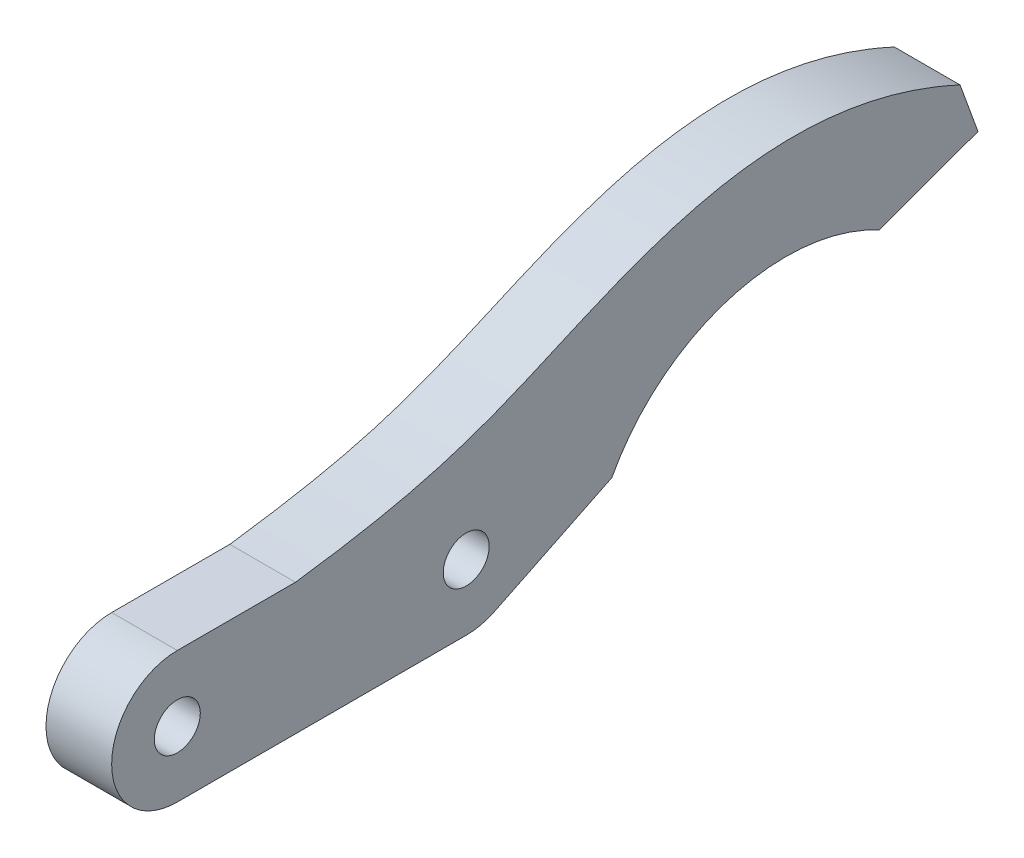
SolidWorks part; units mm, degrees
ref_plane "Front Plane" through (0, 0, 0) normal (0, 0, 1) x (1, 0, 0)
ref_plane "Top Plane" through (0, 0, 0) normal (0, 1, 0) x (1, 0, 0)
ref_plane "Right Plane" through (0, 0, 0) normal (1, 0, 0) x (0, 0, -1)
sketch "Sketch1" plane through (0, 0, 0) normal (1, 0, 0) x (0, 0, -1)
  line L0 (5, 10) -> (27, 10)
  line L1 (27, 0) -> (5, 0)
  circle A0 centre (5, 5) radius 5
  circle A1 centre (5, 5) radius 1.75
  circle A2 centre (27, 5) radius 1.75
  circle A3 centre (27, 5) radius 5
  point P11 (0, 0)
  point P12 (27, 10)
  point P13 (5, 0)
  dimension "D1" = 3.5
  dimension "D2" = 3.5
  dimension "D3" = 22
  dimension "D5" = 10
  dimension "D6" = 10
  dimension "D4" = 5
  dimension "D7" = 5
extrude "Boss-Extrude1" add sketch "Sketch1" along normal blind 5 contours A0 A1 | A3 L0 A0 L1 | A3 A2
sketch "Sketch2" plane through (5, 0, 0) normal (1, 0, 0) x (0, 0, -1)
  line L0 (64.6076, 17.4949) -> (65.9757, 13.7362)
  line L1 (65.9757, 13.7362) -> (58.4582, 11)
  line L2 (5, 0) -> (27, 0)
  line L3 (27, 10) -> (5, 10)
  line L4 (5, 0) -> (27, 0)
  line L5 (27, 10) -> (5, 10)
  line L6 (38.0899, 4.8459) -> (29.1919, 0.506)
  line L7 (0, 0) -> (63.3717, 0) construction
  arc A0 (58.4582, 11) -> (38.0899, 4.8459) centre (51.3324, -2.1994) ccw
  arc A2 (5, 10) -> (5, 0) centre (5, 5) ccw
  arc A3 (27, 0) -> (27, 10) centre (27, 5) ccw
  arc A4 (5, 10) -> (5, 0) centre (5, 5) ccw
  arc A5 (27, 0) -> (27, 10) centre (27, 5) ccw
  spline S0 degree 3 poles (14, 10) (22.7297, 11.1657) (34.5651, 15.0599) (50.5566, 24.0019) (64.6076, 17.4949) knots 0 0 0 0 0.349113 1 1 1 1
  arc M12 (27, 0) -> (27, 10) centre (27, 5) ccw
  line M13 (27, 10) -> (5, 10)
  dimension "D2" = 15
  dimension "D6" = 52.7
  dimension "D12" = 20
  dimension "D3" = 4
  dimension "D4" = 8
  dimension "D5" = 9.9
  dimension "D7" = 14
  dimension "D8" = 4.5
  dimension "D9" = 4.5
  dimension "D10" = 70
  dimension "D11" = 26
  dimension "D13" = 20
  dimension "D14" = 11
  dimension "D1" = 0
extrude "Boss-Extrude2" add sketch "Sketch2" against normal up to surface (5 mm away) contours S0 L6 A0 L1 L0 M13 M12 up to face at (0, 5, -6.75)
